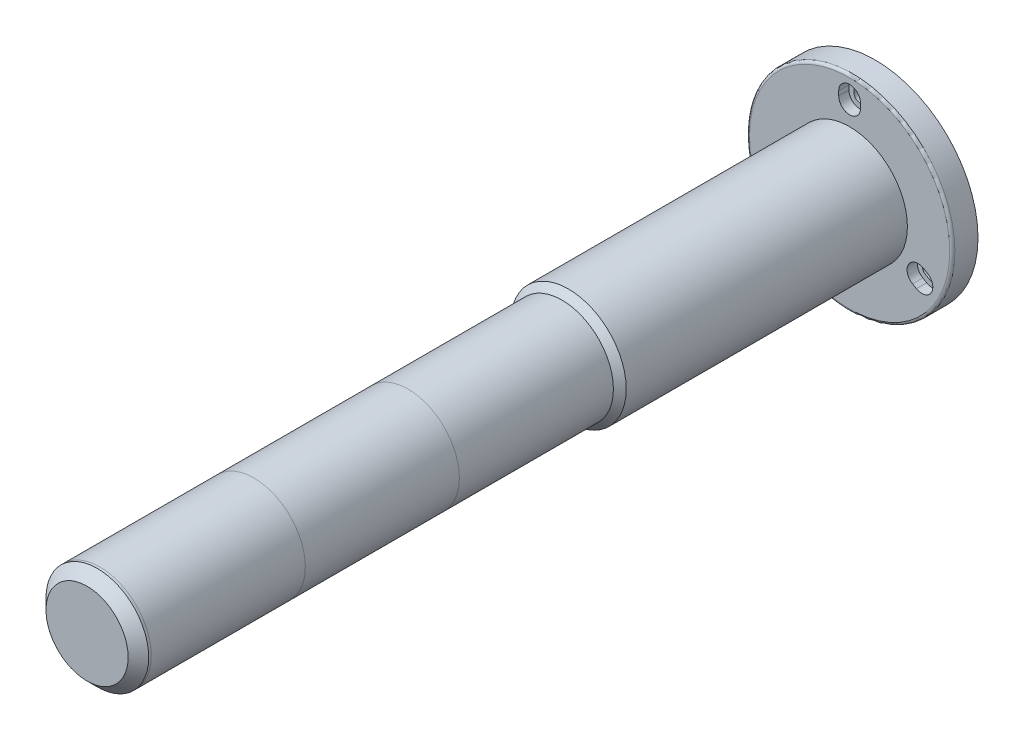
SolidWorks part; units mm, degrees
ref_plane "前基準面" through (0, 0, 0) normal (0, 0, 1) x (1, 0, 0)
ref_plane "上基準面" through (0, 0, 0) normal (0, 1, 0) x (1, 0, 0)
ref_plane "右基準面" through (0, 0, 0) normal (1, 0, 0) x (0, 0, -1)
sketch "草圖1" plane through (0, 0, 0) normal (0, 0, 1) x (1, 0, 0)
  line L0 (0, 44.4144) -> (0, 0) construction
  line L1 (0, 0) -> (43.2927, 0) construction
  line L2 (0, 31.625) -> (-7.1601, 31.625) construction
  line L3 (2.25, 32.5) -> (2.25, 30.75)
  line L4 (-2.25, 32.5) -> (-2.25, 30.75)
  line L5 (29.2708, -13.5514) -> (27.7553, -12.6764)
  line L6 (27.0208, -17.4486) -> (25.5053, -16.5736)
  line L7 (-26.3713, -17.8236) -> (-24.8558, -16.9486)
  line L8 (-28.6213, -13.9264) -> (-27.1058, -13.0514)
  line L9 (-27.4963, -15.875) -> (-25.9808, -15) construction
  line L10 (-25.9808, -15) -> (0, 0) construction
  circle A0 centre (0, 0) radius 40
  circle A1 centre (0, 0) radius 31.625 construction
  arc A2 (2.25, 32.5) -> (-2.25, 32.5) centre (0, 32.5) ccw
  arc A3 (-2.25, 30.75) -> (2.25, 30.75) centre (0, 30.75) ccw
  circle A4 centre (0, 31.625) radius 2.25 construction
  arc A5 (27.7553, -12.6764) -> (25.5053, -16.5736) centre (26.6303, -14.625) ccw
  arc A6 (27.0208, -17.4486) -> (29.2708, -13.5514) centre (28.1458, -15.5) ccw
  arc A7 (-24.8558, -16.9486) -> (-27.1058, -13.0514) centre (-25.9808, -15) ccw
  arc A8 (-28.6213, -13.9264) -> (-26.3713, -17.8236) centre (-27.4963, -15.875) ccw
  circle A9 centre (0, 0) radius 30.75 construction
  circle A10 centre (0, 0) radius 32.5 construction
  dimension "D1" = 80
  dimension "D2" = 61.5
  dimension "D3" = 65
  dimension "D4" = 4.5
extrude "伸長1" add sketch "草圖1" along normal blind 10
fillet "圓角1" radius 1 1 edges at (40, 0, 10)
sketch "草圖2" plane through (0, 0, 10) normal (0, 0, 1) x (1, 0, 0)
  line L2 (24.5049, -18.2498) -> (26.0205, -19.1248)
  line L3 (30.2705, -11.7636) -> (28.7549, -10.8886)
  line L4 (4.25, 30.75) -> (4.25, 32.5)
  line L5 (-4.25, 32.5) -> (-4.25, 30.75)
  line L6 (4.25, 30.75) -> (4.25, 32.5)
  line L7 (-4.25, 32.5) -> (-4.25, 30.75)
  line L8 (-28.0576, -11.2912) -> (-29.5732, -12.1662)
  line L9 (-25.3232, -19.5274) -> (-23.8076, -18.6524)
  arc A2 (26.0205, -19.1248) -> (30.2705, -11.7636) centre (28.1455, -15.4442) ccw
  arc A3 (28.7549, -10.8886) -> (24.5049, -18.2498) centre (26.6299, -14.5692) ccw
  arc A4 (4.25, 32.5) -> (-4.25, 32.5) centre (0, 32.5) ccw
  arc A5 (-4.25, 30.75) -> (4.25, 30.75) centre (0, 30.75) ccw
  arc A6 (4.25, 32.5) -> (-4.25, 32.5) centre (0, 32.5) ccw
  arc A7 (-4.25, 30.75) -> (4.25, 30.75) centre (0, 30.75) ccw
  arc A8 (-29.5732, -12.1662) -> (-25.3232, -19.5274) centre (-27.4482, -15.8468) ccw
  arc A9 (-23.8076, -18.6524) -> (-28.0576, -11.2912) centre (-25.9326, -14.9718) ccw
  dimension "D1" = 2
extrude "除料-伸長1" cut sketch "草圖2" against normal blind 4
sketch "草圖3" plane through (0, 0, 10) normal (0, 0, 1) x (1, 0, 0)
  circle A0 centre (0, 0) radius 22.5
  dimension "D1" = 45
extrude "伸長2" add sketch "草圖3" along normal blind 112 separate body
sketch "草圖4" plane through (0, 0, 122) normal (0, 0, 1) x (1, 0, 0)
  circle A0 centre (0, 0) radius 20
  dimension "D1" = 40
extrude "伸長3" add sketch "草圖4" along normal blind 60 separate body
sketch "草圖5" plane through (0, 0, 182) normal (0, 0, 1) x (1, 0, 0)
  circle A1 centre (0, 0) radius 20
  circle A2 centre (0, 0) radius 20
  dimension "D1" = 0
extrude "伸長4" add sketch "草圖5" along normal blind 60 separate body
sketch "草圖6" plane through (0, 0, 242) normal (0, 0, 1) x (1, 0, 0)
  circle A1 centre (0, 0) radius 20
  circle A2 centre (0, 0) radius 20
  dimension "D1" = 0
extrude "伸長5" add sketch "草圖6" along normal blind 60 separate body
sketch "草圖7" plane through (0, 0, 302) normal (0, 0, 1) x (1, 0, 0)
  circle A1 centre (0, 0) radius 20
  circle A2 centre (0, 0) radius 20
  dimension "D1" = 0
extrude "伸長6" add sketch "草圖7" along normal blind 5 separate body
chamfer "導角1" distance 4 angle 45 1 edges at (20, 0, 307)
chamfer "導角2" distance 2.5 angle 45 1 edges at (22.5, 0, 122)
sketch "草圖8" plane through (0, 0, 0) normal (0, 0, -1) x (-1, 0, 0)
  circle A0 centre (0, 0) radius 30.75
  dimension "D1" = 61.5
sketch "草图1" plane through (0, 0, 0) normal (0, 0, -1) x (-1, 0, 0)
  circle A0 centre (0, 0) radius 7.5
  dimension "D1" = 15
extrude "切除-拉伸1" cut sketch "草图1" against normal blind 10
